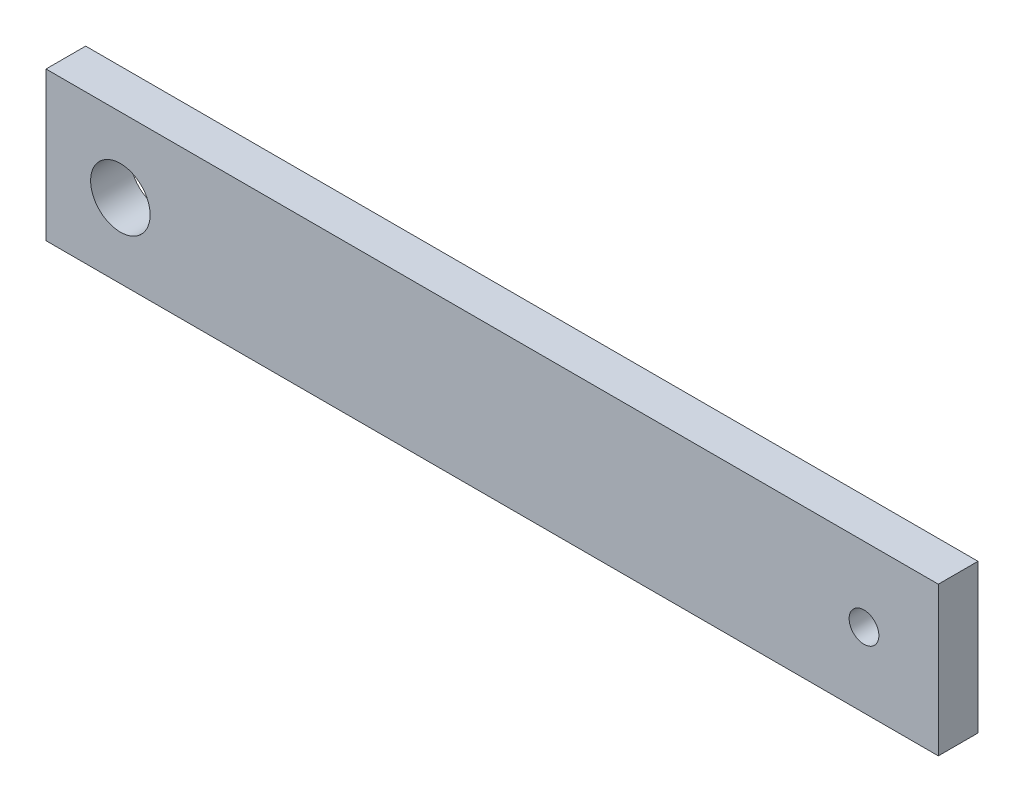
SolidWorks part; units mm, degrees
ref_plane "前视基准面" through (0, 0, 0) normal (0, 0, 1) x (1, 0, 0)
ref_plane "上视基准面" through (0, 0, 0) normal (0, 1, 0) x (1, 0, 0)
ref_plane "右视基准面" through (0, 0, 0) normal (1, 0, 0) x (0, 0, -1)
sketch "草图1" plane through (0, 0, 0) normal (0, 0, 1) x (1, 0, 0)
  line L0 (-106.4945, 0) -> (117.9392, 0) construction
  line L1 (-90, 15) -> (90, 15)
  line L2 (-90, 15) -> (-90, -15)
  line L3 (-90, -15) -> (90, -15)
  line L4 (90, 15) -> (90, -15)
  line L5 (-90, 15) -> (90, -15) construction
  line L6 (-90, -15) -> (90, 15) construction
  circle A0 centre (-75, 0) radius 6
  circle A1 centre (75, 0) radius 3
  point P0 (0, 0)
  dimension "D3" = 12
  dimension "D4" = 6
  dimension "D1" = 30
  dimension "D2" = 180
  dimension "D5" = 75
  dimension "D6" = 75
extrude "凸台-拉伸1" add sketch "草图1" along normal blind 8
